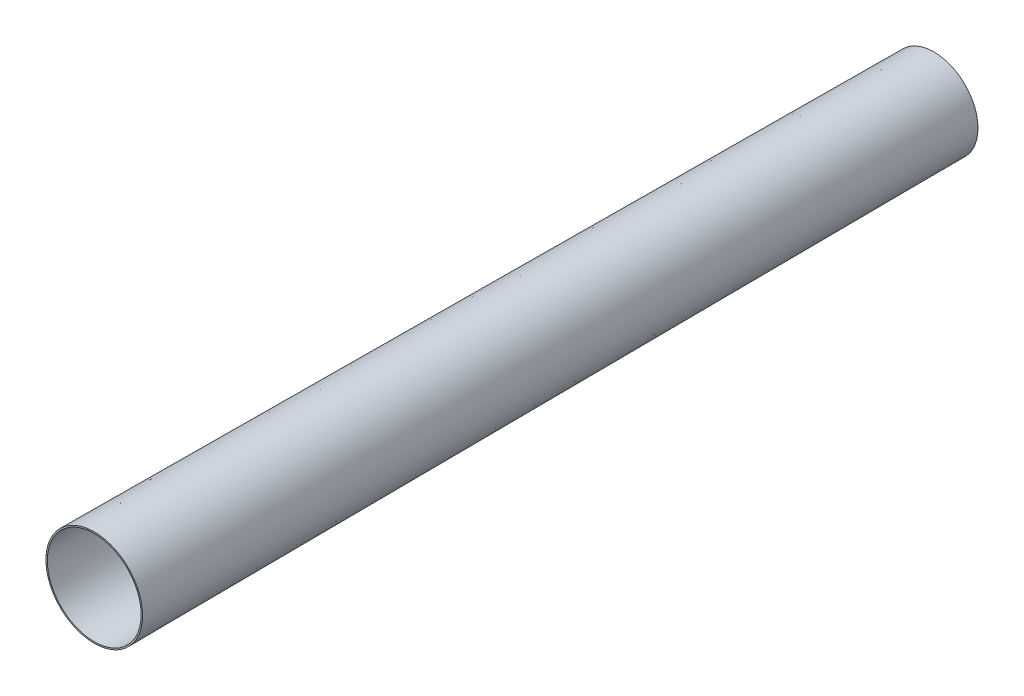
SolidWorks part; units mm, degrees
ref_plane "Front Plane" through (0, 0, 0) normal (0, 0, 1) x (1, 0, 0)
ref_plane "Top Plane" through (0, 0, 0) normal (0, 1, 0) x (1, 0, 0)
ref_plane "Right Plane" through (0, 0, 0) normal (1, 0, 0) x (0, 0, -1)
sketch "Sketch1" plane through (0, 0, 0) normal (0, 0, 1) x (1, 0, 0)
  circle A0 centre (0, 0) radius 15.3156
  circle A1 centre (0, 0) radius 15.8156
  dimension "D2" = 31.6312
  dimension "D1" = 0.5
ref_plane "Plane1" through (0, 0, 301.84) normal (0, 0, 1) x (1, 0, 0)
sketch "Sketch2" plane through (0, 0, 301.84) normal (0, 0, 1) x (1, 0, 0)
  circle A0 centre (0, 0) radius 17.3661
  circle A1 centre (0, 0) radius 16.8661
  dimension "D2" = 34.7323
  dimension "D1" = 0.5
loft "Loft1" add section "Sketch1" section "Sketch2"
shell "Shell1" thickness 0.5
